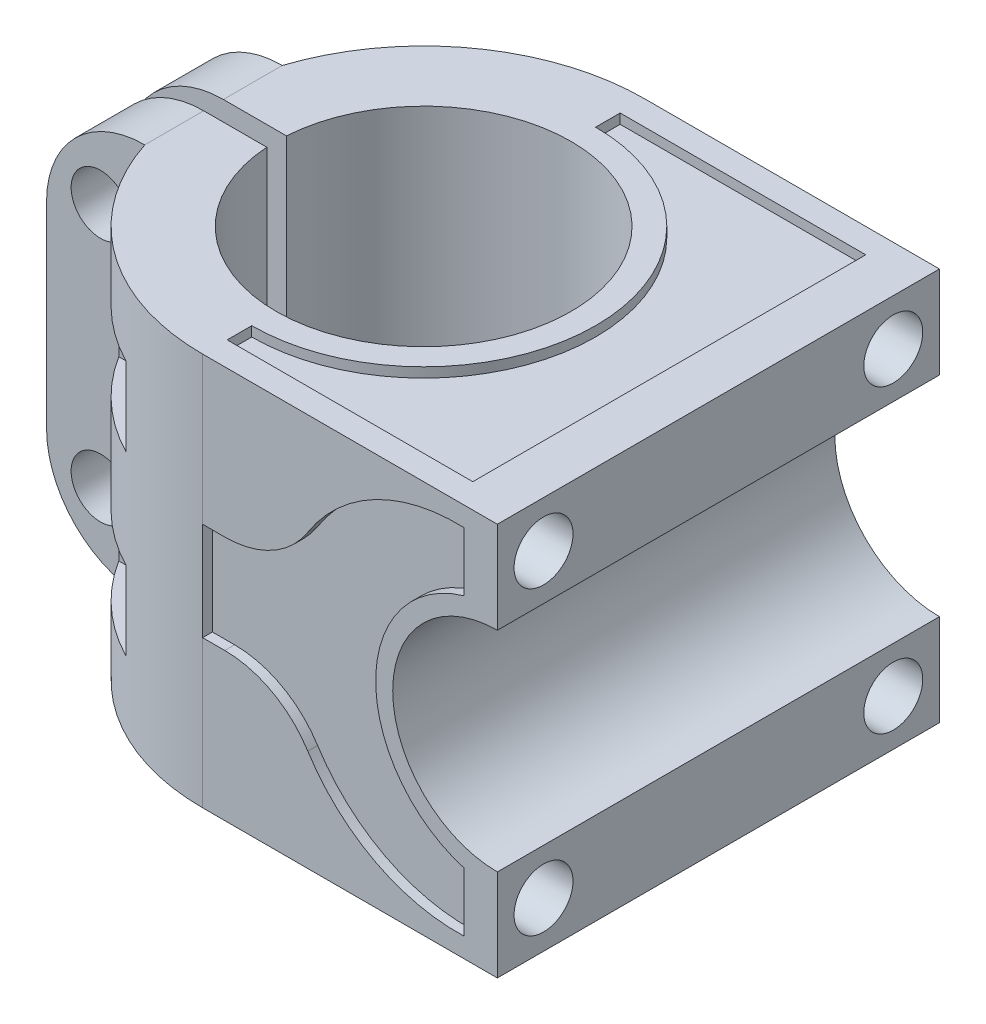
SolidWorks part; units mm, degrees
ref_plane "Front Plane" through (0, 0, 0) normal (0, 0, 1) x (1, 0, 0)
ref_plane "Top Plane" through (0, 0, 0) normal (0, 1, 0) x (1, 0, 0)
ref_plane "Right Plane" through (0, 0, 0) normal (1, 0, 0) x (0, 0, -1)
sketch "Sketch1" plane through (0, 0, 0) normal (0, 1, 0) x (1, 0, 0)
  line L0 (0, 22.5) -> (30, 22.5)
  line L1 (0, -22.5) -> (30, -22.5)
  line L2 (30, -22.5) -> (30, 22.5)
  line L4 (-14.9666, 1) -> (-31.3834, 1)
  line L6 (-14.9666, -1) -> (-31.3834, -1)
  line L7 (-31.3834, -1) -> (-31.3834, -7)
  line L8 (-31.3834, -7) -> (-21.3834, -7)
  line L10 (-31.3834, 7) -> (-21.3834, 7)
  line L11 (-31.3834, 1) -> (-31.3834, 7)
  arc A0 (-14.9666, -1) -> (-14.9666, 1) centre (0, 0) ccw
  arc A1 (0, 22.5) -> (-21.3834, 7) centre (0, 0) ccw
  arc A2 (-21.3834, -7) -> (0, -22.5) centre (0, 0) ccw
  point P3 (30, 0)
  dimension "D1" = 30
  dimension "D2" = 45
  dimension "D3" = 45
  dimension "D4" = 30
  dimension "D5" = 6
  dimension "D6" = 6
  dimension "D7" = 10
  dimension "D8" = 1
  dimension "D9" = 1
extrude "Boss-Extrude1" add sketch "Sketch1" along normal blind 40 contours L6 A2 L1 L2 L0 A1 L4 A0
fillet "Fillet1" radius 10 4 edges at (-31.3834, 40, -4) (-31.3834, 0, -4) (-31.3834, 0, 4) (-31.3834, 40, 4)
sketch "Sketch2" plane through (0, 0, 7) normal (0, 0, 1) x (1, 0, 0)
  line L0 (-31.3834, 30) -> (-31.3834, 10) construction
  circle A0 centre (-25.8834, 32.5) radius 3
  circle A1 centre (-25.8834, 7.5) radius 3
  dimension "D4" = 6
  dimension "D1" = 7.5
  dimension "D2" = 7.5
  dimension "D3" = 5.5
extrude "Cut-Extrude1" cut sketch "Sketch2" against normal blind 30
sketch "Sketch4" plane through (0, 0, 0) normal (0, 0, 1) x (1, 0, 0)
  line L0 (30, 40) -> (30, 0) construction
  circle A0 centre (30, 20) radius 10.65
  point P5 (30, 20)
  dimension "D1" = 21.3
extrude "Cut-Extrude2" cut sketch "Sketch4" against normal through all both and the other way through all
sketch "Sketch3" plane through (30, 0, 0) normal (1, 0, 0) x (0, 0, -1)
  line L0 (-22.5, 40) -> (-22.5, 30.65) construction
  line L1 (-22.5, 0) -> (22.5, 0) construction
  line L2 (-22.5, 40) -> (22.5, 40) construction
  line L3 (22.5, 40) -> (22.5, 30.65) construction
  circle A0 centre (-17.8, 35.3) radius 3
  circle A1 centre (17.8, 35.3) radius 3
  circle A2 centre (17.8, 4.7) radius 3
  circle A3 centre (-17.8, 4.7) radius 3
  dimension "D1" = 6
  dimension "D2" = 4.7
  dimension "D3" = 4.7
  dimension "D4" = 4.7
  dimension "D5" = 4.7
extrude "Cut-Extrude3" cut sketch "Sketch3" against normal blind 15
sketch "Sketch10" plane through (-31.3834, 0, 0) normal (-1, 0, 0) x (0, 0, 1)
  line L0 (-7, 40) -> (-7, 0) construction
  line L1 (-12, 33) -> (-20, 33)
  line L2 (-12, 33) -> (-12, 25)
  line L3 (-12, 25) -> (-20, 25)
  line L4 (-20, 33) -> (-20, 25)
  line L5 (12, 33) -> (20, 33)
  line L6 (12, 33) -> (12, 25)
  line L7 (12, 25) -> (20, 25)
  line L8 (20, 33) -> (20, 25)
  line L9 (12, 15) -> (20, 15)
  line L10 (12, 15) -> (12, 7)
  line L11 (12, 7) -> (20, 7)
  line L12 (20, 15) -> (20, 7)
  line L13 (-20, 15) -> (-12, 15)
  line L14 (-20, 15) -> (-20, 7)
  line L15 (-20, 7) -> (-12, 7)
  line L16 (-12, 15) -> (-12, 7)
  line L17 (7, 40) -> (7, 0) construction
  point P22 (-7, 20)
  dimension "D1" = 8
  dimension "D2" = 12
  dimension "D3" = 5
  dimension "D4" = 5
  dimension "D5" = 5
extrude "Cut-Extrude4" cut sketch "Sketch10" against normal blind 22
sketch "Sketch11" plane through (0, 40, 0) normal (0, 1, 0) x (1, 0, 0)
  line L0 (0, -1000) -> (0, 49000) construction
  line L1 (25, 20) -> (25, -20)
  line L2 (25, 20) -> (0, 20)
  line L3 (0, 20) -> (0, 17.5)
  line L4 (25, -20) -> (0, -20)
  line L5 (0, -20) -> (0, -17.5)
  arc A0 (0, -17.5) -> (0, 17.5) centre (0, 0) ccw
  point P7 (25, 0)
  dimension "D1" = 35
  dimension "D2" = 40
  dimension "D3" = 25
extrude "Cut-Extrude5" cut sketch "Sketch11" against normal blind 1
sketch "Sketch14" plane through (0, 0, 22.5) normal (0, 0, 1) x (1, 0, 0)
  line L0 (0, 40) -> (0, 0) construction
  point P0 (0, 20)
  point P3 (0, 20)
  line B0 (0, 25) -> (2.2603, 25)
  line B1 (26.6166, 38) -> (26.6166, 32)
  line B2 (26.6166, 8) -> (26.6166, 2)
  line B3 (2.2603, 15) -> (0, 15)
  line B4 (0, 15) -> (0, 25)
  arc B5 (10.7074, 29.6478) -> (2.2603, 25) centre (2.2603, 35) cw
  arc B6 (10.7074, 29.6478) -> (26.6166, 38) centre (25.9122, 20.0138) cw
  arc B7 (26.6166, 8) -> (26.6166, 32) centre (30.1166, 20) cw
  arc B8 (26.6166, 2) -> (10.7074, 10.3522) centre (25.9122, 19.9862) cw
  arc B9 (2.2603, 15) -> (10.7074, 10.3522) centre (2.2603, 5) cw
sketch_block_instance "Block2-2"
sketch_block "Block2"
extrude "Cut-Extrude6" cut sketch "Sketch14" against normal blind 1
mirror "Mirror3" about plane through (0, 0, 0) normal (0, 0, 1) of "Cut-Extrude6"
ref_plane "Plane3" through (0, 20, 0) normal (0, 1, 0) x (1, 0, 0)
mirror "Mirror4" about plane through (0, 20, 0) normal (0, 1, 0) of "Cut-Extrude5"
